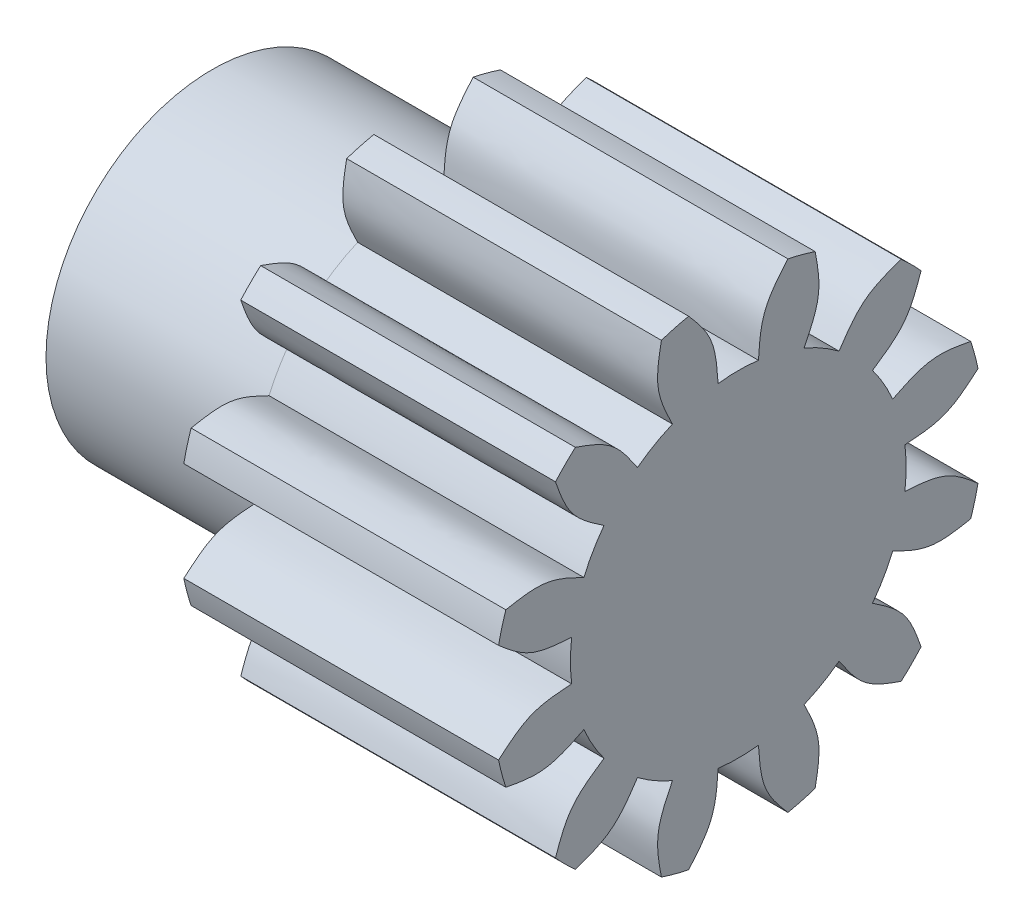
SolidWorks part; units mm, degrees
ref_plane "Front" through (0, 0, 0) normal (0, 0, 1) x (1, 0, 0)
ref_plane "Top" through (0, 0, 0) normal (0, 1, 0) x (1, 0, 0)
ref_plane "Right" through (0, 0, 0) normal (1, 0, 0) x (0, 0, -1)
sketch "Ritning 1" plane through (0, 0, 0) normal (0, 0, 1) x (1, 0, 0)
  line L0 (12.5, 1) -> (2.5, 1)
  line L1 (2.5, 1) -> (2.5, 3.5)
  line L2 (2.5, 3.5) -> (-12.5, 3.5)
  line L3 (12.5, 1) -> (12.5, -3.5)
  line L4 (-12.5, 3.5) -> (-12.5, -3.5)
  line L5 (-12.5, -3.5) -> (12.5, -3.5)
  dimension "D1" = 2.5
  dimension "D2" = 12.5
  dimension "D3" = 12.5
  dimension "D4" = 1
  dimension "D5" = 3.5
  dimension "D6" = 3.5
revolve "Kugghjulsämne" add sketch "Ritning 1" angle 360 about L5
sketch "Ritning 2" plane through (-12.5, 0, 0) normal (-1, 0, 0) x (0, 0, 1)
  line L0 (0, -3.5) -> (0, 3.5) construction
  line L1 (1.4199, 3.3545) -> (0, 4.7744)
  line L2 (-1.4199, 3.3545) -> (0, 4.7744)
  line L3 (0, -3.5) -> (1.4199, -3.5) construction
  arc A0 (0.5768, 1.2652) -> (-0.5768, 1.2652) centre (0, -3.5) ccw
  circle A1 centre (0, -3.5) radius 7 construction
  spline S0 degree 3 poles (1.4199, 3.3545) (1.173, 3.0671) (0.6581, 2.4675) (0.6046, 1.6769) (0.5768, 1.2652) knots 0 0 0 0 0.479362 1 1 1 1
  spline S1 degree 3 poles (-1.4199, 3.3545) (-1.173, 3.0671) (-0.6581, 2.4675) (-0.6046, 1.6769) (-0.5768, 1.2652) knots 0 0 0 0 0.479362 1 1 1 1
  dimension "D1" = 4.8
  dimension "D2" = 0.5768
  dimension "D3" = 0.7854
  dimension "D4" = 1.4199
  dimension "D5" = 5.9484
  dimension "D6" = 0.7854
  dimension "D7" = 6.8545
extrude "Kugglucka" cut sketch "Ritning 2" against normal up to surface (15 mm away) up to face at (2.5, -3.5, 7)
pattern_circular "CirPattern" count 12 over 360 about axis through (-12.5, -3.5, 0) along (-1, 0, 0) of "Kugglucka"
sketch "Sketch1" plane through (-12.5, 0, 0) normal (-1, 0, 0) x (0, 0, 1)
  line L0 (-1.25, -1.6302) -> (-1.25, -5.3719)
  line L1 (0, 1.3) -> (0, -8.3) construction
  arc A0 (-1.25, -5.3719) -> (-1.25, -1.6302) centre (0, -3.5011) ccw
  arc A1 (0.5768, 1.2652) -> (-0.5768, 1.2652) centre (0, -3.5) ccw construction
  arc A2 (-0.5768, -8.2652) -> (0.5768, -8.2652) centre (0, -3.5) ccw construction
  dimension "D1" = 4.5
  dimension "D2" = 1.25
extrude "Cut-Extrude1" cut sketch "Sketch1" against normal blind 6
sketch "Sketch2" plane through (12.5, 0, 0) normal (1, 0, 0) x (0, 0, -1)
  circle A1 centre (0, -3.5) radius 4.5
  circle A2 centre (0, -3.5) radius 4.5
  dimension "D1" = 0
extrude "Cut-Extrude2" cut sketch "Sketch2" against normal up to surface (10 mm away) up to face at (2.5, -3.5, 0)
sketch "Sketch4" plane through (-12.5, 0, 0) normal (-1, 0, 0) x (0, 0, 1)
  circle A0 centre (2.4488, -7.6373) radius 0.0076
  circle A1 centre (0.0413, -3.4784) radius 7.4561
  circle A2 centre (0.0413, -3.4784) radius 4.7534
extrude "Cut-Extrude4" cut sketch "Sketch4" against normal blind 6
sketch "Sketch5" plane through (0, 0, 0) normal (0, 0, 1) x (1, 0, 0)
  line L0 (-12.5, 1.275) -> (-12.5, -8.2319) construction
  circle A0 centre (-9.5, -3.1593) radius 1.5
  dimension "D1" = 3
  dimension "D2" = 3
extrude "Cut-Extrude5" cut sketch "Sketch5" against normal blind 6
